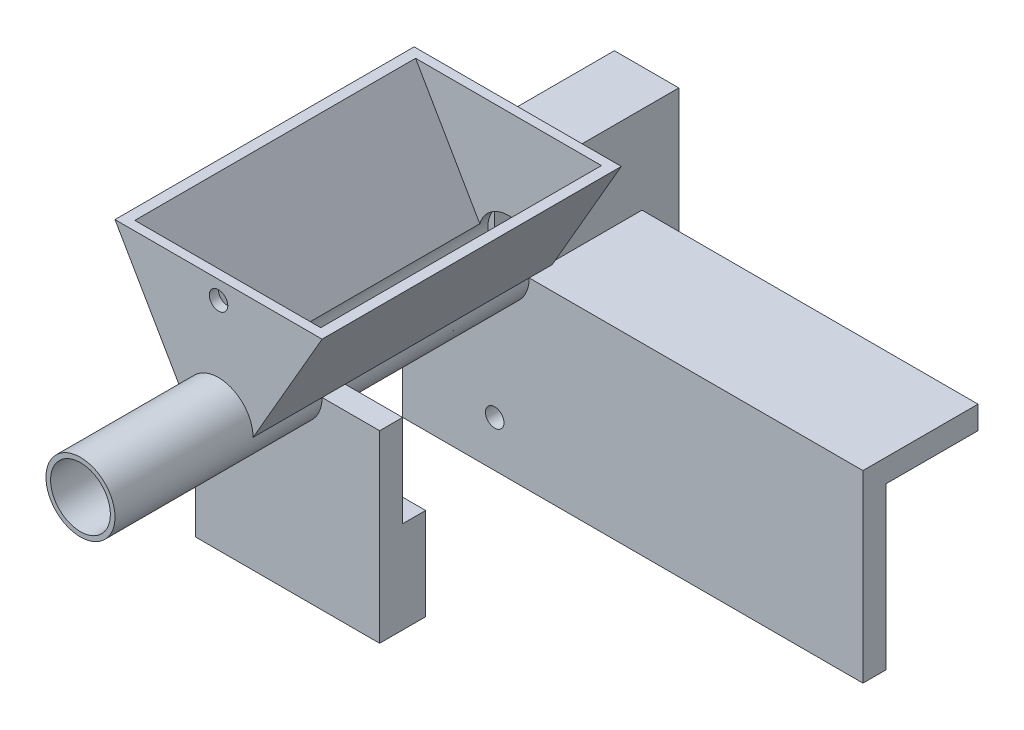
SolidWorks part; units mm, degrees
ref_plane "Front Plane" through (0, 0, 0) normal (0, 0, 1) x (1, 0, 0)
ref_plane "Top Plane" through (0, 0, 0) normal (0, 1, 0) x (1, 0, 0)
ref_plane "Right Plane" through (0, 0, 0) normal (1, 0, 0) x (0, 0, -1)
sketch "Sketch2" plane through (0, 0, 0) normal (0, 0, 1) x (1, 0, 0)
  line L0 (9.525, 0) -> (28.575, 32.9956)
  line L1 (28.575, 32.9956) -> (-28.575, 32.9956)
  line L2 (-28.575, 32.9956) -> (-9.525, 0)
  line L3 (55, 0) -> (-55, 0) construction
  arc A0 (-9.525, 0) -> (9.525, 0) centre (0, 0) ccw
  dimension "D1" = 19.05
  dimension "D2" = 38.1
  dimension "D3" = 120
  dimension "D4" = 120
extrude "Boss-Extrude1" add sketch "Sketch2" along normal mid plane 82.55
shell "Shell1" thickness 2.54
sketch "Sketch3" plane through (0, 0, 41.275) normal (0, 0, 1) x (1, 0, 0)
  circle A0 centre (0, 0) radius 9.525
  dimension "D1" = 19.05
extrude "Boss-Extrude2" add sketch "Sketch3" along normal blind 38.1
sketch "Sketch5" plane through (0, 0, -41.275) normal (0, 0, -1) x (-1, 0, 0)
  line L0 (-101.6, 0) -> (25.4, 0)
  line L1 (55, 0) -> (-55, 0) construction
  line L2 (25.4, 0) -> (25.4, -50.8)
  line L3 (25.4, -50.8) -> (-101.6, -50.8)
  line L4 (-101.6, -50.8) -> (-101.6, 0)
  point P6 (0, 0)
  dimension "D1" = 50.8
  dimension "D2" = 127
extrude "Boss-Extrude3" add sketch "Sketch5" against normal blind 6.35
ref_plane "Plane1" through (0, 0, 15.875) normal (0, 0, 1) x (1, 0, 0)
sketch "Sketch6" plane through (0, 0, 15.875) normal (0, 0, 1) x (1, 0, 0)
  line L0 (-25.4, 0) -> (25.4, 0)
  line L1 (55, 0) -> (-55, 0) construction
  line L2 (25.4, 0) -> (25.4, -50.8)
  line L3 (25.4, -50.8) -> (-25.4, -50.8)
  line L4 (-25.4, -50.8) -> (-25.4, 0)
  point P8 (0, 0)
  dimension "D1" = 50.8
  dimension "D2" = 50.8
extrude "Boss-Extrude4" add sketch "Sketch6" along normal blind 6.35
sketch "Sketch4" plane through (0, 0, 79.375) normal (0, 0, 1) x (1, 0, 0)
  circle A0 centre (0, 0) radius 8.255
  dimension "D1" = 16.51
extrude "Cut-Extrude1" cut sketch "Sketch4" against normal through all
sketch "Sketch18" plane through (0, 0, 41.275) normal (0, 0, 1) x (1, 0, 0)
  line L0 (0, 32.9956) -> (0, 27.9681) construction
  line L1 (28.575, 32.9956) -> (-28.575, 32.9956) construction
hole_wizard "1/4-20 Tapped Hole1" positions "Sketch19" profile "Sketch20" tap size "1/4-20" standard "ANSI Inch"
sketch "Sketch19" plane through (0, 0, 41.275) normal (0, 0, 1) x (1, 0, 0)
  point P0 (0, 27.9681)
sketch "Sketch20" plane through (0, 27.9681, 41.275) normal (1, 0, 0) x (0, -1, 0)
  line L0 (0, 0) -> (0, 2.54)
  line L1 (0, 2.54) -> (2.5527, 2.54)
  line L2 (2.5527, 2.54) -> (2.5527, 0)
  line L5 (2.5527, 0) -> (0, 0)
  line L11 (0, -6.35) -> (0, 107.95) construction
  dimension "Thru Tap Drill Dia." = 5.1054
  dimension "Thru Tap Drill Depth" = 2.54
cosmetic thread "Hole Thread1" parameters "D2"=6.35
sketch "Sketch21" plane through (0, 0, -41.275) normal (0, 0, -1) x (-1, 0, 0)
  line L0 (0, -50.8) -> (0, -38.1) construction
  line L1 (-101.6, -50.8) -> (25.4, -50.8) construction
  dimension "D1" = 12.7
hole_wizard "1/4-20 Tapped Hole2" positions "Sketch22" profile "Sketch23" tap size "1/4-20" standard "ANSI Inch"
sketch "Sketch22" plane through (0, 0, -41.275) normal (0, 0, -1) x (-1, 0, 0)
  point P0 (0, -38.1)
sketch "Sketch23" plane through (0, -38.1, -41.275) normal (1, 0, 0) x (0, 1, 0)
  line L0 (0, 0) -> (0, 6.35)
  line L1 (0, 6.35) -> (2.5527, 6.35)
  line L2 (2.5527, 6.35) -> (2.5527, 0)
  line L5 (2.5527, 0) -> (0, 0)
  line L11 (0, -6.35) -> (0, 107.95) construction
  dimension "Thru Tap Drill Dia." = 5.1054
  dimension "Thru Tap Drill Depth" = 6.35
cosmetic thread "Hole Thread2" parameters "D2"=6.35
sketch "Sketch24" plane through (0, 0, 15.875) normal (0, 0, -1) x (-1, 0, 0)
  line L0 (25.4, 0) -> (25.4, -50.8) construction
  line L1 (-25.4, -50.8) -> (25.4, -50.8)
  line L2 (-25.4, -50.8) -> (-25.4, -25.4)
  line L3 (-25.4, -25.4) -> (25.4, -25.4)
  line L4 (25.4, -50.8) -> (25.4, -25.4)
extrude "Boss-Extrude5" add sketch "Sketch24" along normal blind 6.35
sketch "Sketch25" plane through (0, 0, -41.275) normal (0, 0, -1) x (-1, 0, 0)
  line L1 (-8.89, 24.13) -> (8.89, 24.13)
  line L2 (-8.89, 24.13) -> (-8.89, -13.97)
  line L3 (-8.89, -13.97) -> (8.89, -13.97)
  line L4 (8.89, 24.13) -> (8.89, -13.97)
  line L5 (-8.89, 24.13) -> (8.89, -13.97) construction
  line L6 (-8.89, -13.97) -> (8.89, 24.13) construction
  point P0 (0, 5.08)
  point P6 (0, 0)
  point P7 (0, 0)
  point P8 (0, 0)
  dimension "D1" = 17.78
  dimension "D2" = 38.1
extrude "Boss-Extrude6" add sketch "Sketch25" along normal blind 35.56
sketch "Sketch26" plane through (0, 0, -76.835) normal (0, 0, -1) x (-1, 0, 0)
  line L0 (8.89, 24.13) -> (-8.89, 24.13) construction
  line L1 (-6.35, -13.97) -> (6.35, -13.97)
  line L2 (-6.35, -13.97) -> (-6.35, 21.59)
  line L3 (-6.35, 21.59) -> (6.35, 21.59)
  line L4 (6.35, -13.97) -> (6.35, 21.59)
  line L5 (-6.35, -13.97) -> (6.35, 21.59) construction
  line L6 (-6.35, 21.59) -> (6.35, -13.97) construction
  line L7 (8.89, -13.97) -> (8.89, 24.13) construction
  line L8 (-8.89, -13.97) -> (8.89, -13.97) construction
  line L9 (-8.89, 24.13) -> (-8.89, -13.97) construction
  point P0 (0, 3.81)
  dimension "D1" = 2.54
  dimension "D2" = 2.54
  dimension "D3" = 0
  dimension "D4" = 2.54
extrude "Cut-Extrude2" cut sketch "Sketch26" against normal up to surface (35.56 mm away) up to face at (8.255, 0, -41.275)
sketch "Sketch27" plane through (0, 0, -41.275) normal (0, 0, -1) x (-1, 0, 0)
  line L0 (-6.35, 5.2747) -> (-6.35, 21.59) construction
  line L1 (6.35, 21.59) -> (-6.35, 21.59)
  line L2 (6.35, 21.59) -> (6.35, 16.51)
  line L3 (6.35, 16.51) -> (-6.35, 16.51)
  line L4 (-6.35, 21.59) -> (-6.35, 16.51)
  line L5 (-6.35, -13.97) -> (-6.35, -5.2747) construction
  line L6 (-6.35, -11.43) -> (6.35, -11.43)
  line L7 (-6.35, -11.43) -> (-6.35, -6.35)
  line L8 (-6.35, -6.35) -> (6.35, -6.35)
  line L9 (6.35, -11.43) -> (6.35, -6.35)
  line L10 (6.35, -5.2747) -> (6.35, -13.97) construction
  line L11 (-8.89, -13.97) -> (-6.35, -13.97) construction
  dimension "D1" = 5.08
  dimension "D2" = 2.54
  dimension "D3" = 5.08
extrude "Boss-Extrude7" add sketch "Sketch27" along normal blind 11.43
sketch "Sketch28" plane through (0, 0, -41.275) normal (0, 0, -1) x (-1, 0, 0)
  line L0 (-8.89, 24.13) -> (-8.89, -13.97) construction
  line L1 (-8.89, 0) -> (-101.6, 0)
  line L2 (-8.89, 0) -> (-8.89, -6.35)
  line L3 (-8.89, -6.35) -> (-101.6, -6.35)
  line L4 (-101.6, 0) -> (-101.6, -6.35)
  line L5 (-101.6, 0) -> (-101.6, -50.8) construction
  line L6 (-9.525, 0) -> (-101.6, 0) construction
  dimension "D1" = 6.35
extrude "Boss-Extrude8" add sketch "Sketch28" along normal blind 25.4
